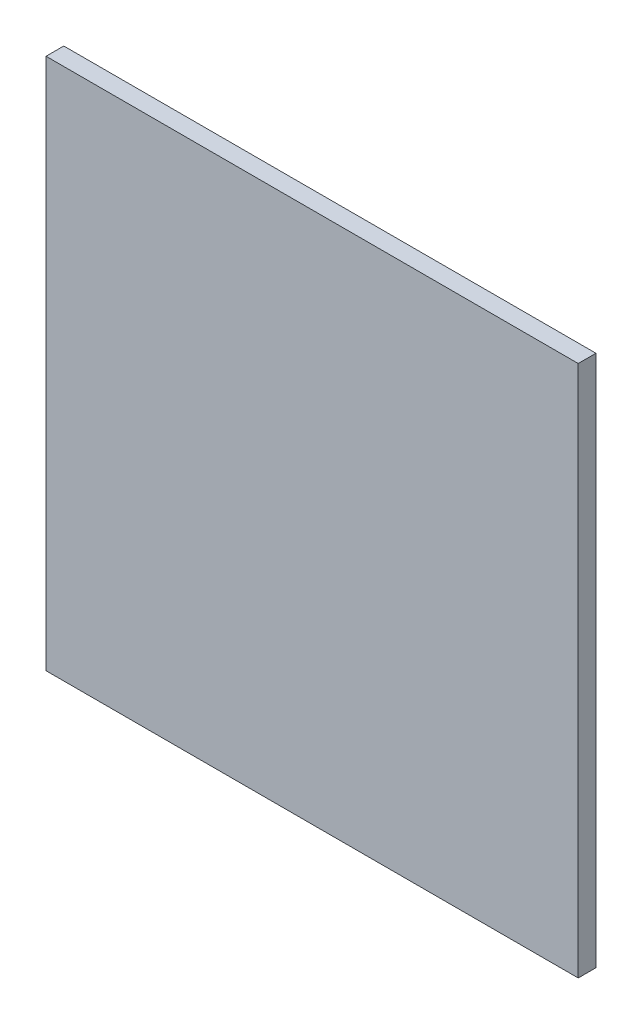
SolidWorks part; units mm, degrees
ref_plane "Front Plane" through (0, 0, 0) normal (0, 0, 1) x (1, 0, 0)
ref_plane "Top Plane" through (0, 0, 0) normal (0, 1, 0) x (1, 0, 0)
ref_plane "Right Plane" through (0, 0, 0) normal (1, 0, 0) x (0, 0, -1)
sketch "Sketch2" plane through (0, 0, 0) normal (0, 0, 1) x (1, 0, 0)
  line L2 (-0.3, -0.3) -> (0.3, -0.3)
  line L3 (-0.3, -0.3) -> (-0.3, 0.3)
  line L4 (-0.3, 0.3) -> (0.3, 0.3)
  line L5 (0.3, -0.3) -> (0.3, 0.3)
  line L6 (-0.3, -0.3) -> (0.3, 0.3) construction
  line L7 (-0.3, 0.3) -> (0.3, -0.3) construction
  point P0 (0, 0)
  dimension "D1" = 0.6
  dimension "D2" = 0.6
extrude "Boss-Extrude1" add sketch "Sketch2" along normal mid plane 0.02
